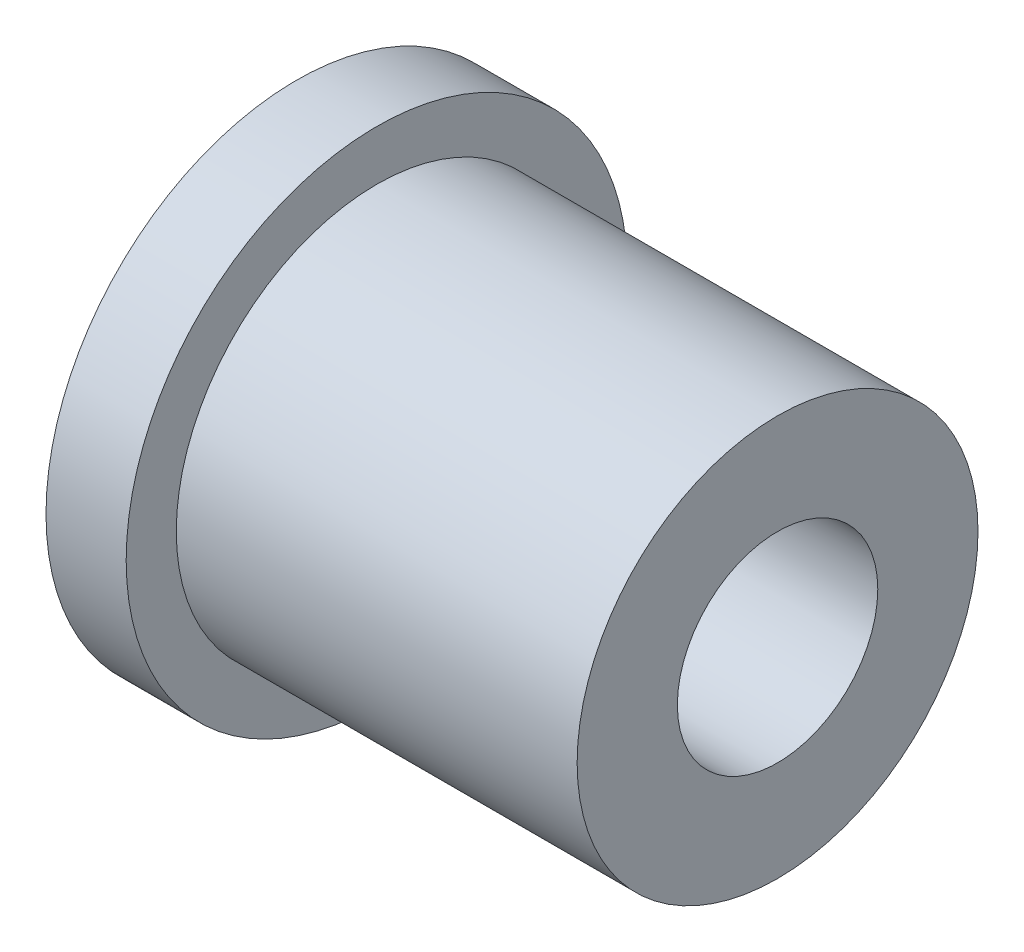
SolidWorks part; units mm, degrees
material "7075-T6 (SN)"
ref_plane "Front Plane" through (0, 0, 0) normal (0, 0, 1) x (1, 0, 0)
ref_plane "Top Plane" through (0, 0, 0) normal (0, 1, 0) x (1, 0, 0)
ref_plane "Right Plane" through (0, 0, 0) normal (1, 0, 0) x (0, 0, -1)
sketch "Sketch1" plane through (0, 0, 0) normal (0, 0, 1) x (1, 0, 0)
  line L0 (0, 3.175) -> (0, 7.9375)
  line L1 (0, 7.9375) -> (2.54, 7.9375)
  line L2 (2.54, 7.9375) -> (2.54, 6.35)
  line L3 (2.54, 6.35) -> (15.24, 6.35)
  line L4 (15.24, 6.35) -> (15.24, 3.175)
  line L5 (0, 0) -> (15.24, 0) construction
  line L6 (0, 3.175) -> (15.24, 3.175)
  point P9 (0, 0)
  dimension "D1" = 7.9375
  dimension "D2" = 2.54
  dimension "D3" = 12.7
  dimension "D4" = 6.35
  dimension "D5" = 3.175
revolve "Revolve1" add sketch "Sketch1" angle 360 about L5
